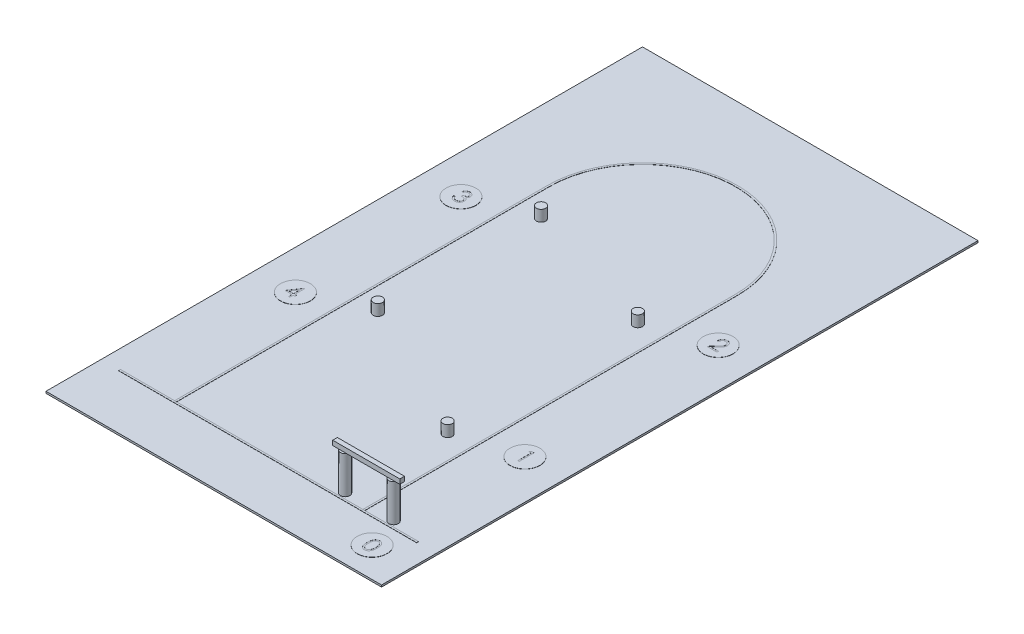
SolidWorks part; units mm, degrees
ref_plane "Front" through (0, 0, 0) normal (0, 0, 1) x (1, 0, 0)
ref_plane "Top" through (0, 0, 0) normal (0, 1, 0) x (1, 0, 0)
ref_plane "Right" through (0, 0, 0) normal (1, 0, 0) x (0, 0, -1)
sketch "草圖1" plane through (0, 0, 0) normal (0, 1, 0) x (1, 0, 0)
  line L0 (500, 0) -> (500, 2000)
  line L1 (-500, 2000) -> (-500, 0)
  line L2 (-500, 0) -> (500, 0) construction
  arc A0 (500, 2000) -> (-500, 2000) centre (0, 2000) ccw
  dimension "D3" = 500
  dimension "D1" = 2000
  dimension "D2" = 2000
extrude "伸長-薄件1" add sketch "草圖1" along normal blind 1 thin
sketch "草圖2" plane through (0, 0, 0) normal (0, -1, 0) x (-1, 0, 0)
  line L1 (-900, -300) -> (900, -300)
  line L2 (-900, -300) -> (-900, 2900)
  line L3 (-900, 2900) -> (900, 2900)
  line L4 (900, -300) -> (900, 2900)
  dimension "D1" = 3200
  dimension "D2" = 1800
  dimension "D3" = 300
  dimension "D4" = 400
extrude "填料-伸長1" add sketch "草圖2" along normal blind 10 separate body
sketch "草圖3" plane through (0, 0, 0) normal (0, 1, 0) x (1, 0, 0)
  line L0 (798.3498, 0) -> (-800.2824, 0)
extrude "伸長-薄件2" add sketch "草圖3" along normal blind 1 separate body thin thin type one direction reverse wall 10
sketch "草圖4" plane through (0, 0, 0) normal (0, 1, 0) x (1, 0, 0)
  line L0 (0, 828) -> (0, 0) construction
  line L5 (510, 0) -> (510, 2000) construction
  line L6 (-510, 2000) -> (-510, 0) construction
  circle A0 centre (690, 679.319) radius 80
  circle A2 centre (690, 1716) radius 80
  circle A3 centre (-690, 1716) radius 80
  circle A4 centre (-690, 828) radius 80
  circle A5 centre (690, -140.5086) radius 80
  point P17 (690, 627.8615)
  point P18 (690, 658.9021)
  point P19 (690, 679.319)
  dimension "D1" = 160
  dimension "D2" = 180
  dimension "D3" = 180
  dimension "D5" = 180
  dimension "D6" = 180
  dimension "D7" = 180
  dimension "D4" = 828
extrude "填料-伸長2" add sketch "草圖4" along normal blind 1 separate body
sketch "草圖5" plane through (0, 1, 0) normal (0, 1, 0) x (1, 0, 0)
  text T0 "1" font "Century Gothic" height in points 300
  text T1 "2" font "Century Gothic" height in points 300
  text T2 "3" font "Century Gothic" height in points 300
  text T3 "4" font "Century Gothic" height in points 300
  text T4 "0\r\n" font "Century Gothic" height in points 300
  point P3 (648.1227, 619.0267)
  point P4 (640.842, 614.3453)
  point P6 (661.6483, 642.4338)
  point P7 (661.6483, 1675.4703)
  point P8 (0, 0)
  point P10 (0, 0)
  point P11 (661.6483, 1680.5684)
  point P12 (-717.8181, 1680.5684)
  point P13 (-720.6169, 1675.2981)
  point P14 (-717.1184, 1680.5684)
  point P15 (-717.1184, 796.6432)
  point P16 (0, 0)
  point P17 (-725.4779, 791.7839)
  point P18 (-729.5273, 790.1642)
  point P19 (661.6483, -169.8413)
  point P20 (661.6483, -181.5231)
extrude "除料-伸長1" cut sketch "草圖5" against normal blind 0.5
sketch "草圖6" plane through (0, 0, 0) normal (0, 1, 0) x (1, 0, 0)
  line L0 (375, 1600.0783) -> (375, 579.6765) construction
  line L1 (-375, 1830.8188) -> (-375, 955.1632) construction
  line L2 (500, 0) -> (500, 2000) construction
  line L3 (-500, 2000) -> (-500, 0) construction
  line L4 (510, 0) -> (510, 2000) construction
  line L5 (798.3498, 0) -> (-800.2824, 0) construction
  circle A0 centre (375, 579.6765) radius 25
  circle A1 centre (375, 1600.0783) radius 25
  circle A2 centre (-375, 1830.8188) radius 25
  circle A3 centre (-375, 955.1632) radius 25
  circle A4 centre (375, 30) radius 25 construction
  circle A5 centre (635, 30) radius 25 construction
  point P20 (375, 1600.0783)
  point P21 (-375, 1830.8188)
  dimension "D1" = 50
  dimension "D4" = 125
  dimension "D5" = 125
  dimension "D6" = 30
  dimension "D7" = 30
  dimension "D2" = 125
  dimension "D3" = 125
extrude "填料-伸長3" add sketch "草圖6" along normal blind 60 separate body
sketch "草圖8" plane through (0, 0, 0) normal (0, 1, 0) x (1, 0, 0)
  circle A0 centre (375, 30) radius 24.9909
  circle A1 centre (635, 30) radius 25.2108
extrude "填料-伸長5" add sketch "草圖8" along normal blind 200 separate body
sketch "草圖7" plane through (0, 200, 0) normal (0, 1, 0) x (1, 0, 0)
  line L1 (321.298, 41.7277) -> (681.298, 41.7277)
  line L2 (321.298, 41.7277) -> (321.298, 16.7277)
  line L3 (321.298, 16.7277) -> (681.298, 16.7277)
  line L4 (681.298, 41.7277) -> (681.298, 16.7277)
  point P4 (705.7394, 15.243)
  point P5 (388.8323, 18.124)
  point P6 (653.3156, 16.8701)
  point P7 (681.298, 16.7277)
  dimension "D1" = 25
  dimension "D2" = 360
extrude "填料-伸長4" add sketch "草圖7" along normal blind 25
